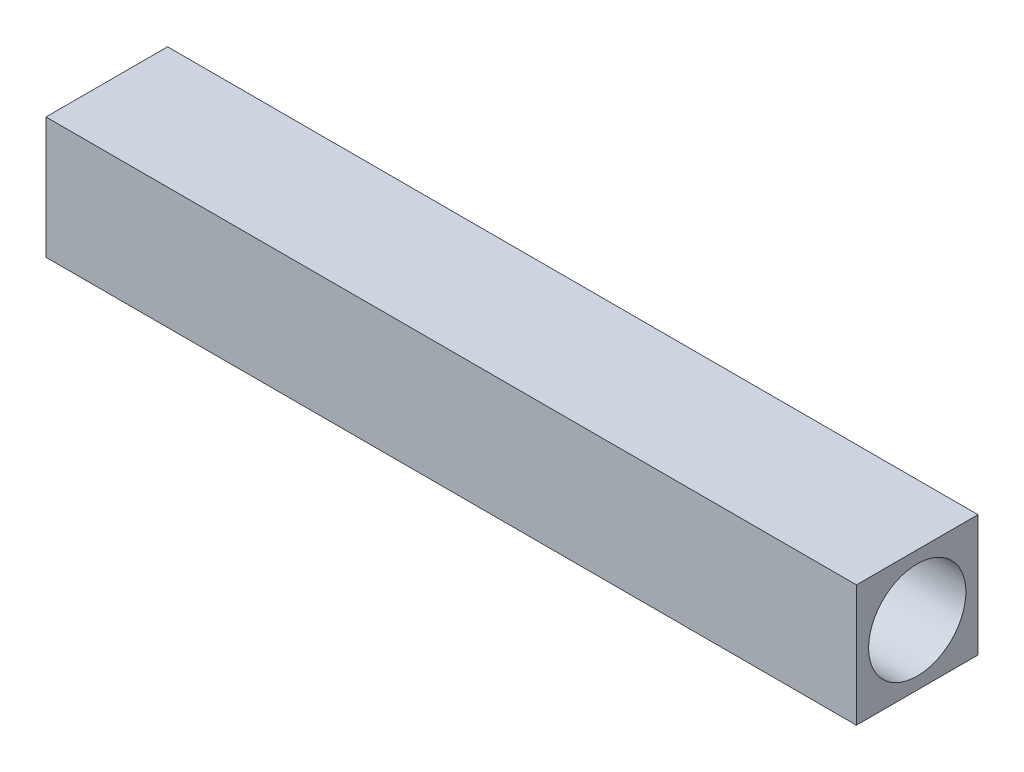
SolidWorks part; units mm, degrees
ref_plane "Front Plane" through (0, 0, 0) normal (0, 0, 1) x (1, 0, 0)
ref_plane "Top Plane" through (0, 0, 0) normal (0, 1, 0) x (1, 0, 0)
ref_plane "Right Plane" through (0, 0, 0) normal (1, 0, 0) x (0, 0, -1)
sketch "Sketch1" plane through (0, 0, 0) normal (1, 0, 0) x (0, 0, -1)
  line L1 (0, 0) -> (-95.25, 0)
  line L2 (0, 0) -> (0, 95.25)
  line L3 (0, 95.25) -> (-95.25, 95.25)
  line L4 (-95.25, 0) -> (-95.25, 95.25)
  circle A0 centre (-47.625, 47.625) radius 38.1
  point P7 (-47.625, 95.25)
  point P8 (0, 47.625)
  dimension "D3" = 76.2
  dimension "D1" = 95.25
  dimension "D2" = 95.25
extrude "Boss-Extrude1" add sketch "Sketch1" along normal mid plane 635
